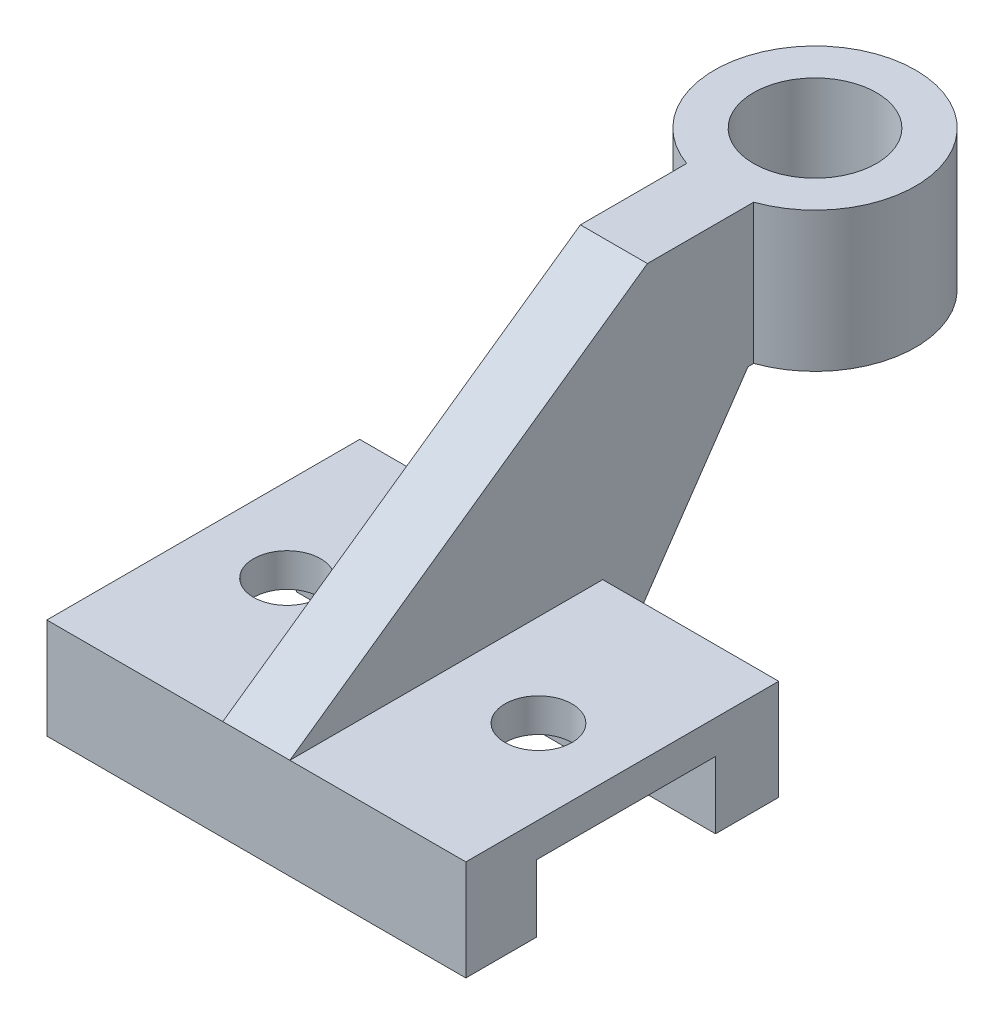
SolidWorks part; units mm, degrees
ref_plane "Front Plane" through (0, 0, 0) normal (0, 0, 1) x (1, 0, 0)
ref_plane "Top Plane" through (0, 0, 0) normal (0, 1, 0) x (1, 0, 0)
ref_plane "Right Plane" through (0, 0, 0) normal (1, 0, 0) x (0, 0, -1)
sketch "Sketch1" plane through (0, 0, 0) normal (1, 0, 0) x (0, 0, -1)
  line L0 (-1016.5319, -597.6314) -> (-694.178, -597.6314)
  line L1 (-694.178, -597.6314) -> (-694.178, -292.8314)
  line L2 (-694.178, -292.8314) -> (118.622, -292.8314)
  line L3 (118.622, -292.8314) -> (118.622, -597.6314)
  line L4 (-1016.5319, -597.6314) -> (-1016.5319, -140.4314)
  line L5 (-1016.5319, -140.4314) -> (405.8681, -140.4314)
  line L6 (405.8681, -140.4314) -> (405.8681, -597.6314)
  line L7 (405.8681, -597.6314) -> (118.622, -597.6314)
  dimension "D1" = 304.8
  dimension "D2" = 457.2
  dimension "D3" = 304.8
  dimension "D4" = 1422.4
  dimension "D5" = 812.8
  dimension "D6" = 287.2461
extrude "Boss-Extrude1" add sketch "Sketch1" along normal blind 1905 contours L7 L3 L2 L1 L0 L4 L5 L6
ref_plane "Plane1" through (0, 1002.5686, 0) normal (0, 1, 0) x (1, 0, 0)
sketch "Sketch6" plane through (0, 1002.5686, 0) normal (0, 1, 0) x (1, 0, 0)
  line L0 (1905, -1016.5319) -> (0, -1016.5319) construction
  circle A0 centre (952.5, 1523.4681) radius 457.2
  circle A1 centre (952.5, 1523.4681) radius 279.4
  point P5 (952.5, -1016.5319)
  dimension "D1" = 914.4
  dimension "D2" = 558.8
  dimension "D3" = 2540
extrude "Boss-Extrude2" add sketch "Sketch6" against normal blind 635 separate body
sketch "Sketch8" plane through (0, 1002.5686, 0) normal (0, 1, 0) x (1, 0, 0)
  line L1 (952.5, 1066.2681) -> (952.5, 609.0681)
  point P0 (0, 0)
ref_plane "Plane2" through (952.5, 0, 0) normal (1, 0, 0) x (0, 0, -1)
sketch "Sketch10" plane through (952.5, 0, 0) normal (1, 0, 0) x (0, 0, -1)
  line L0 (609.0681, 1002.5686) -> (-1016.5319, -140.4314)
  line L1 (1066.2681, 1002.5686) -> (1066.2681, 367.5686)
  line L2 (1066.2681, 367.5686) -> (405.8681, -597.6314)
  line L3 (609.0681, 1002.5686) -> (1066.2681, 1002.5686)
  line L4 (-1016.5319, -140.4314) -> (405.8681, -140.4314)
  line L5 (405.8681, -140.4314) -> (405.8681, -597.6314)
extrude "Boss-Extrude3" add sketch "Sketch10" along normal blind 152.4 and the other way blind 152.4
sketch "Sketch11" plane through (0, -140.4314, 0) normal (0, 1, 0) x (1, 0, 0)
  line L0 (800.1, -1016.5319) -> (0, -1016.5319) construction
  line L1 (1905, -1016.5319) -> (1104.9, -1016.5319) construction
  line L2 (1905, -1016.5319) -> (1905, 405.8681) construction
  line L3 (0, -694.178) -> (0, 118.622) construction
  circle A0 centre (1524, -305.3319) radius 152.4
  circle A1 centre (381, -305.3319) radius 152.4
  dimension "D1" = 711.2
  dimension "D3" = 304.8
  dimension "D2" = 381
  dimension "D4" = 381
  dimension "D5" = 711.2
extrude "Cut-Extrude1" cut sketch "Sketch11" against normal up to next (152.4 mm away)
sketch "Sketch12" plane through (0, 0, -1066.2681) normal (0, 0, -1) x (-1, 0, 0)
  line L0 (-1104.9, 1002.5686) -> (-800.1, 1002.5686)
  line L1 (-800.1, 1002.5686) -> (-800.1, 367.5686)
  line L2 (-800.1, 367.5686) -> (-1104.9, 367.5686)
  line L3 (-1104.9, 367.5686) -> (-1104.9, 1002.5686)
extrude "Boss-Extrude6" add sketch "Sketch12" along normal blind 152.4
sketch "Sketch7" plane through (0, 1002.5686, 0) normal (0, 1, 0) x (1, 0, 0)
